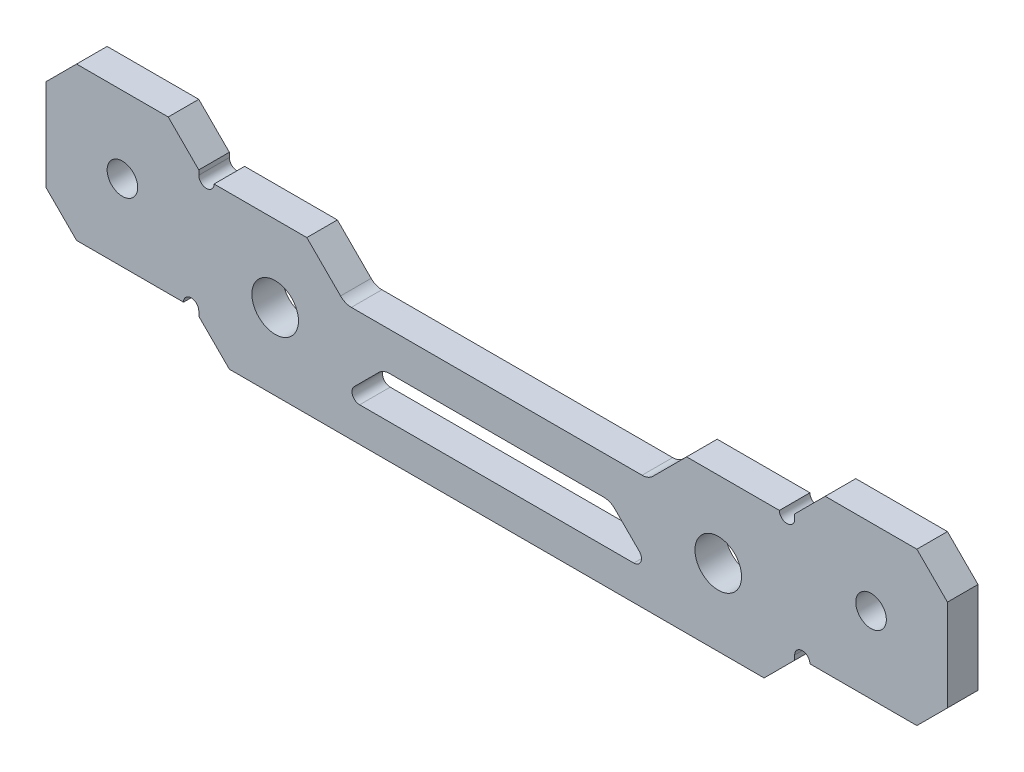
SolidWorks part; units mm, degrees
ref_plane "前视基准面" through (0, 0, 0) normal (0, 0, 1) x (1, 0, 0)
ref_plane "上视基准面" through (0, 0, 0) normal (0, 1, 0) x (1, 0, 0)
ref_plane "右视基准面" through (0, 0, 0) normal (1, 0, 0) x (0, 0, -1)
sketch "草图1" plane through (0, 0, 0) normal (0, 0, 1) x (1, 0, 0)
  line L0 (29, 0) -> (-29, 0) construction
  line L1 (0, 0) -> (0, 10) construction
  line L2 (-39, 10) -> (39, 10)
  line L3 (-39, -10) -> (39, -10)
  line L4 (-39, -10) -> (-39, -5.4)
  line L5 (-39, -5.4) -> (-59, -5.4)
  line L6 (-59, -5.4) -> (-59, 14.6)
  line L7 (-59, 14.6) -> (-39, 14.6)
  line L8 (-39, 14.6) -> (-39, 10)
  line L9 (39, 14.6) -> (39, 10)
  line L10 (59, 14.6) -> (39, 14.6)
  line L11 (59, -5.4) -> (59, 14.6)
  line L12 (39, -5.4) -> (59, -5.4)
  line L13 (39, -10) -> (39, -5.4)
  circle A0 centre (-29, 0) radius 3.05
  circle A1 centre (29, 0) radius 3.05
  circle A2 centre (-49, 4.6) radius 2
  circle A3 centre (49, 4.6) radius 2
  point P4 (0, 0)
  point P24 (0, -10)
  dimension "D2" = 6.1
  dimension "D3" = 4.6
  dimension "D4" = 20
  dimension "D5" = 4
  dimension "D8" = 10
  dimension "D9" = 10
  dimension "D1" = 58
  dimension "D6" = 10
  dimension "D7" = 20
  dimension "D10" = 20
  dimension "D11" = 10
extrude "凸台-拉伸1" add sketch "草图1" along normal mid plane 4
sketch "草图2" plane through (0, 0, 2) normal (0, 0, 1) x (1, 0, 0)
  line L0 (39, 10) -> (-39, 10) construction
  line L1 (-59, -5.4) -> (-39, -5.4) construction
  line L2 (39, -5.4) -> (59, -5.4) construction
  line L3 (-24.8579, 10) -> (-19.8579, 5)
  line L4 (-19.8579, 5) -> (19.8579, 5)
  line L5 (19.8579, 5) -> (24.8579, 10)
  line L6 (24.8579, 10) -> (-24.8579, 10)
  circle A0 centre (-38, 10) radius 1
  circle A1 centre (-40, -5.4) radius 1
  circle A2 centre (38, 10) radius 1
  circle A3 centre (40, -5.4) radius 1
  circle A4 centre (-29, 0) radius 3.05 construction
  point P24 (0, 10)
  dimension "D1" = 2
  dimension "D2" = 10
  dimension "D3" = 5
  dimension "D4" = 135
extrude "切除-拉伸1" cut sketch "草图2" against normal through all
chamfer "倒角1" distance 4 angle 45 8 edges at (39, 14.6, 0) (59, 14.6, 0) (59, -5.4, 0) (39, -10, 0) (-39, -10, 0) (-39, 14.6, 0) (-59, -5.4, 0) (-59, 14.6, 0)
sketch "草图3" plane through (0, 0, 2) normal (0, 0, 1) x (1, 0, 0)
  line L0 (-14.8579, 0) -> (-20.3579, -5.5)
  line L1 (-20.3579, -5.5) -> (20.3579, -5.5)
  line L2 (20.3579, -5.5) -> (14.8579, 0)
  line L3 (14.8579, 0) -> (-14.8579, 0)
  line L4 (-19.8579, 5) -> (19.8579, 5) construction
  line L5 (-35, -10) -> (35, -10) construction
  circle A0 centre (-29, 0) radius 3.05 construction
  point P6 (0, 0)
  point P7 (0, -5.5)
  dimension "D1" = 10
  dimension "D2" = 5
  dimension "D3" = 4.5
extrude "切除-拉伸2" cut sketch "草图3" against normal through all
fillet "圆角1" radius 1 2 edges at (20.3579, -5.5, 0) (-20.3579, -5.5, 0)
fillet "圆角2" radius 2 4 edges at (19.8579, 5, 0) (-19.8579, 5, 0) (14.8579, 0, 0) (-14.8579, 0, 0)
